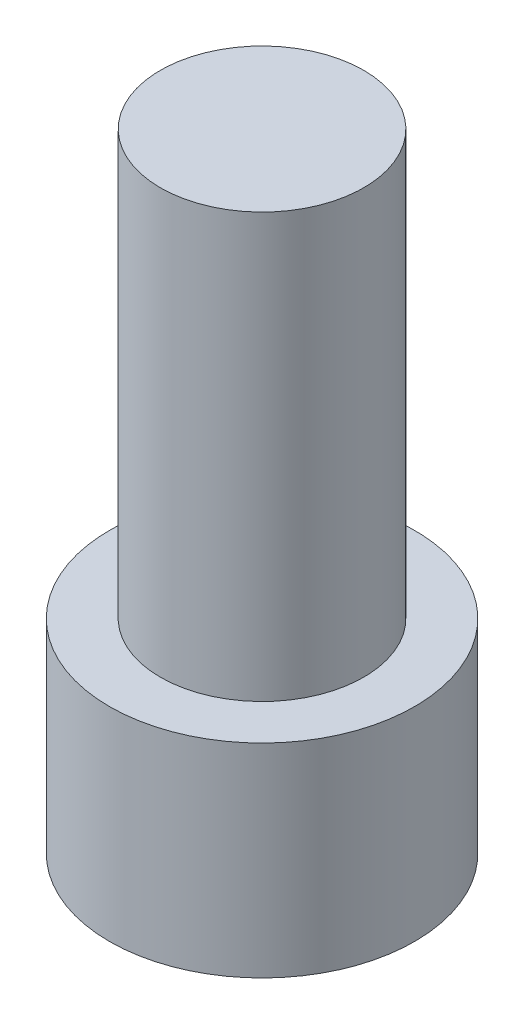
SolidWorks part; units mm, degrees
ref_plane "Front Plane" through (0, 0, 0) normal (0, 0, 1) x (1, 0, 0)
ref_plane "Top Plane" through (0, 0, 0) normal (0, 1, 0) x (1, 0, 0)
ref_plane "Right Plane" through (0, 0, 0) normal (1, 0, 0) x (0, 0, -1)
sketch "Sketch1" plane through (0, 0, 0) normal (0, 1, 0) x (1, 0, 0)
  circle A0 centre (0, 0) radius 9
extrude "Boss-Extrude1" add sketch "Sketch1" along normal blind 12
sketch "Sketch2" plane through (0, 12, 0) normal (0, 1, 0) x (1, 0, 0)
  circle A0 centre (0, 0) radius 6
extrude "Boss-Extrude2" add sketch "Sketch2" along normal blind 25
